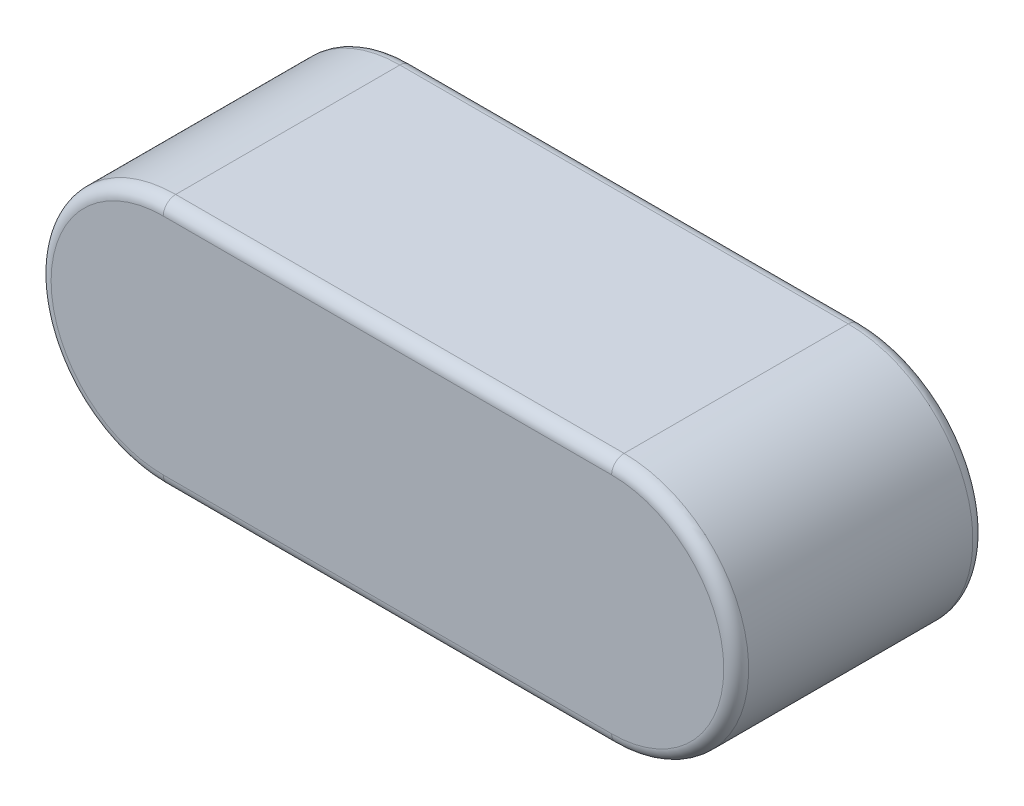
SolidWorks part; units mm, degrees
material "AISI 304"
ref_plane "Front Plane" through (0, 0, 0) normal (0, 0, 1) x (1, 0, 0)
ref_plane "Top Plane" through (0, 0, 0) normal (0, 1, 0) x (1, 0, 0)
ref_plane "Right Plane" through (0, 0, 0) normal (1, 0, 0) x (0, 0, -1)
sketch "Sketch1" plane through (0, 0, 0) normal (0, 0, 1) x (1, 0, 0)
  line L1 (0, 0) -> (9, 0)
  line L2 (0, 0) -> (0, 5) construction
  line L3 (0, 5) -> (9, 5)
  line L4 (9, 0) -> (9, 5) construction
  arc A0 (0, 5) -> (0, 0) centre (0, 2.5) ccw
  arc A1 (9, 0) -> (9, 5) centre (9, 2.5) ccw
  dimension "D1" = 9
  dimension "D2" = 5
extrude "Boss-Extrude1" add sketch "Sketch1" along normal blind 5 contours L2 A0 | L2 A0 | A1 L3 A0 L1 | L4 A1 | L4 A1
fillet "Fillet3" radius 0.25 8 edges at (11.5, 2.5, 0) (11.5, 2.5, 5) (4.5, 5, 0) (4.5, 5, 5) (-2.5, 2.5, 0) (-2.5, 2.5, 5) (4.5, 0, 0) (4.5, 0, 5)
